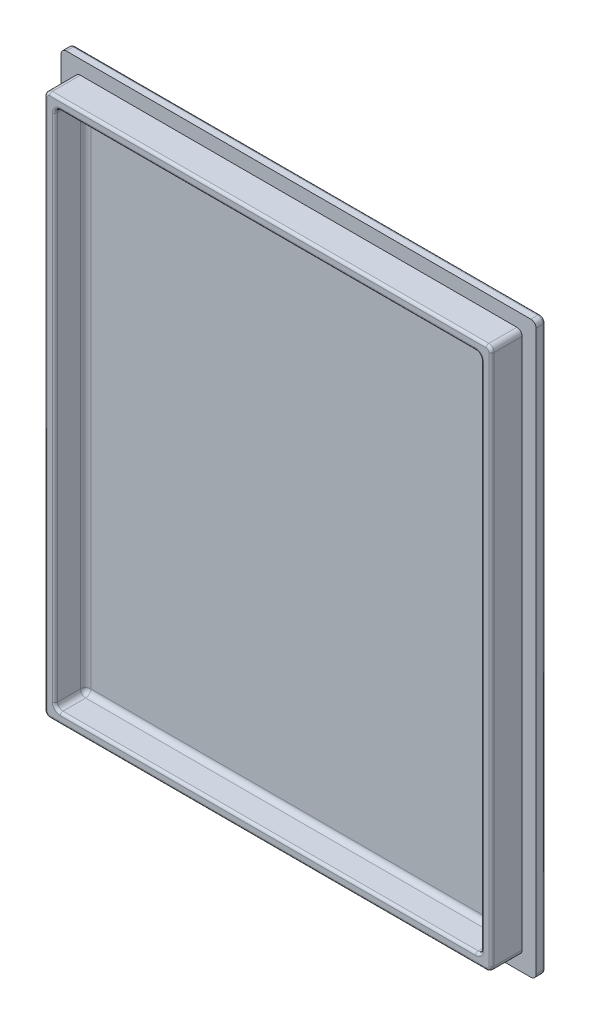
SolidWorks part; units mm, degrees
ref_plane "Front Plane" through (0, 0, 0) normal (0, 0, 1) x (1, 0, 0)
ref_plane "Top Plane" through (0, 0, 0) normal (0, 1, 0) x (1, 0, 0)
ref_plane "Right Plane" through (0, 0, 0) normal (1, 0, 0) x (0, 0, -1)
sketch "Sketch1" plane through (0, 0, 0) normal (0, 0, 1) x (1, 0, 0)
  line L1 (-45, 54) -> (45, 54)
  line L2 (-45, 54) -> (-45, -54)
  line L3 (-45, -54) -> (45, -54)
  line L4 (45, 54) -> (45, -54)
  line L5 (-45, 54) -> (45, -54) construction
  line L6 (-45, -54) -> (45, 54) construction
  point P0 (0, 0)
  dimension "D1" = 108
  dimension "D2" = 90
extrude "Boss-Extrude1" add sketch "Sketch1" along normal blind 1.8
sketch "Sketch2" plane through (0, 0, 1.8) normal (0, 0, 1) x (1, 0, 0)
  line L0 (45, 54) -> (-45, 54) construction
  line L1 (42.35, -51.35) -> (-42.35, -51.35)
  line L2 (42.35, -51.35) -> (42.35, 51.35)
  line L3 (42.35, 51.35) -> (-42.35, 51.35)
  line L4 (-42.35, -51.35) -> (-42.35, 51.35)
  line L5 (42.35, -51.35) -> (-42.35, 51.35) construction
  line L6 (42.35, 51.35) -> (-42.35, -51.35) construction
  line L7 (45, -54) -> (45, 54) construction
  line L9 (40.35, -49.35) -> (-40.35, -49.35)
  line L10 (40.35, -49.35) -> (40.35, 49.35)
  line L11 (40.35, 49.35) -> (-40.35, 49.35)
  line L12 (-40.35, -49.35) -> (-40.35, 49.35)
  line L13 (40.35, -49.35) -> (-40.35, 49.35) construction
  line L14 (40.35, 49.35) -> (-40.35, -49.35) construction
  point P0 (0, 0)
  point P10 (0, 0)
  dimension "D1" = 2.65
  dimension "D2" = 2.65
  dimension "D3" = 2
  dimension "D4" = 2
extrude "Boss-Extrude2" add sketch "Sketch2" along normal blind 5.8
fillet "Fillet1" radius 1 16 edges at (-45, -54, 0.9) (-45, 54, 0.9) (45, -54, 0.9) (40.35, -49.35, 4.7) (40.35, 49.35, 4.7) (-40.35, 49.35, 4.7) (-40.35, -49.35, 4.7) (-42.35, 51.35, 4.7) (42.35, -51.35, 4.7) (-42.35, -51.35, 4.7) (42.35, 51.35, 4.7) (45, 54, 0.9) (0, 49.35, 1.8) (40.35, 0, 1.8) (0, -49.35, 1.8) (-40.35, 0, 1.8)
fillet "Fillet2" radius 0.5 24 edges at (44.7071, -53.7071, 0) (45, 0, 0) (44.7071, 53.7071, 0) (0, 54, 0) (-44.7071, 53.7071, 0) (-45, 0, 0) (-44.7071, -53.7071, 0) (0, -54, 0) (40.0571, -49.0571, 7.6) (40.35, 0, 7.6) (40.0571, 49.0571, 7.6) (0, 49.35, 7.6) (-40.0571, 49.0571, 7.6) (-40.35, 0, 7.6) (-40.0571, -49.0571, 7.6) (0, -49.35, 7.6) (42.0571, 51.0571, 7.6) (42.35, 0, 7.6) (42.0571, -51.0571, 7.6) (0, -51.35, 7.6) (-42.0571, -51.0571, 7.6) (-42.35, 0, 7.6) (-42.0571, 51.0571, 7.6) (0, 51.35, 7.6)
sketch "Sketch3" plane through (0, 0, 0) normal (0, 0, -1) x (-1, 0, 0)
  line L0 (-45, 0) -> (45, 0) construction
  line L1 (-45, -53) -> (-45, 53) construction
  line L2 (45, 53) -> (45, -53) construction
  line L3 (-44.5, 9) -> (44.5, 9) construction
  line L4 (-44.5, 53) -> (-44.5, -53) construction
  line L5 (44.5, -53) -> (44.5, 53) construction
  text T0 "JOULEMETER\r\n100V DC\r\n20A DC" font "Arial Rounded MT Bold" height 7.5
  point P13 (44.5, 12.1257)
  point P14 (0, 0)
  dimension "D1" = 9
extrude "Cut-Extrude1" cut sketch "Sketch3" against normal blind 0.4
